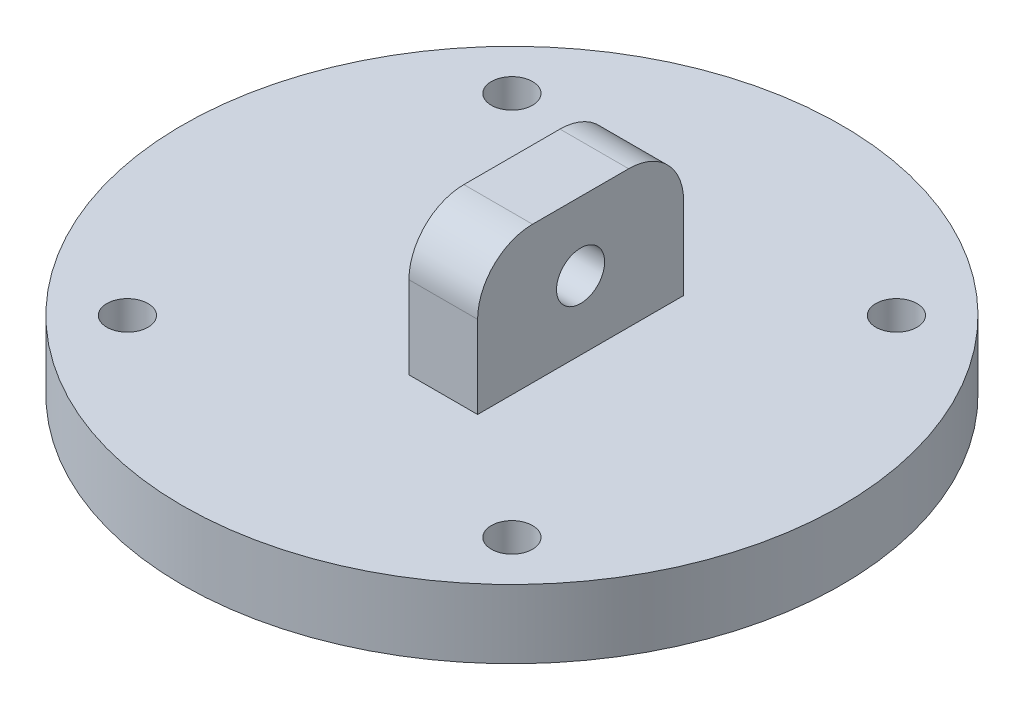
SolidWorks part; units mm, degrees
ref_plane "前视基准面" through (0, 0, 0) normal (0, 0, 1) x (1, 0, 0)
ref_plane "上视基准面" through (0, 0, 0) normal (0, 1, 0) x (1, 0, 0)
ref_plane "右视基准面" through (0, 0, 0) normal (1, 0, 0) x (0, 0, -1)
other "Configuration Table"
sketch "草图1" plane through (0, 0, 0) normal (0, 1, 0) x (1, 0, 0)
  line L0 (0, 34.1) -> (0, -32.0913) construction
  line L15 (-37.5602, 0) -> (46.169, 0) construction
  circle A1 centre (0, 0) radius 24
  dimension "D4" = 48
extrude "凸台-拉伸1" add sketch "草图1" along normal blind 5
sketch "草图2" plane through (0, 0, 0) normal (0, 1, 0) x (1, 0, 0)
  line L1 (-5, 7.5) -> (5, 7.5)
  line L2 (-5, 7.5) -> (-5, -7.5)
  line L3 (-5, -7.5) -> (5, -7.5)
  line L4 (5, 7.5) -> (5, -7.5)
  line L5 (-5, 7.5) -> (5, -7.5) construction
  line L6 (-5, -7.5) -> (5, 7.5) construction
  point P0 (0, 0)
  dimension "D1" = 10
  dimension "D2" = 15
extrude "凸台-拉伸2" add sketch "草图2" along normal blind 15
sketch "草图3" plane through (-5, 0, 0) normal (-1, 0, 0) x (0, 0, 1)
  line L1 (0, 17.9908) -> (0, -1.502) construction
  line L2 (-7.5, 10) -> (7.5, 10)
  line L3 (-7.5, 10) -> (7.5, 10) construction
  circle A0 centre (0, 10) radius 1.75
  dimension "D2" = 3.5
  dimension "D1" = 5
extrude "切除-拉伸1" cut sketch "草图3" against normal up to next
sketch "草图4" plane through (-5, 0, 0) normal (-1, 0, 0) x (0, 0, 1)
  line L1 (-10, 15) -> (10, 15)
  line L2 (-10, 15) -> (-10, 5)
  line L3 (-10, 5) -> (10, 5)
  line L4 (10, 15) -> (10, 5)
  line L5 (-10, 15) -> (10, 5) construction
  line L6 (-10, 5) -> (10, 15) construction
  point P0 (0, 10)
  dimension "D1" = 10
  dimension "D2" = 20
extrude "切除-拉伸2" cut sketch "草图4" against normal blind 5
sketch "草图5" plane through (0, 0, 0) normal (0, -1, 0) x (1, 0, 0)
  line L1 (-14, 14) -> (14, 14) construction
  line L2 (-14, 14) -> (-14, -14) construction
  line L3 (-14, -14) -> (14, -14) construction
  line L4 (14, 14) -> (14, -14) construction
  line L5 (-14, 14) -> (14, -14) construction
  line L6 (-14, -14) -> (14, 14) construction
  point P1 (14, -14)
  point P2 (-14, 14)
  point P3 (-14, -14)
  point P4 (14, 14)
  point P13 (14, -14)
  point P17 (-14, -14)
  point P19 (-14, 14)
  point P21 (14, 14)
  point P27 (0, 0)
  point P28 (0, 0)
  point P29 (0, 0)
  dimension "D1" = 28
  dimension "D2" = 28
hole_wizard "Ø3.0mm 暗销孔1" positions "草图5" profile "草图8" hole size "Ø3.0" standard "GB" end condition up to next
sketch "草图8" plane through (14, 0, 14) normal (1, 0, 0) x (0, 0, -1)
  line L0 (0, 0) -> (0, 5)
  line L1 (0, 5) -> (1.5, 5)
  line L2 (1.5, 5) -> (1.5, 0)
  line L5 (1.5, 0) -> (0, 0)
  line L11 (0, -6.35) -> (0, 107.95) construction
  dimension "通孔孔直径" = 3
  dimension "通孔孔深度" = 5
fillet "圆角1" radius 4 2 edges at (2.5, 15, 7.5) (2.5, 15, -7.5)
sketch "草图9" plane through (0, 0, 0) normal (0, -1, 0) x (1, 0, 0)
  line L0 (0, 72.0219) -> (0, -30.929) construction
  line L5 (-35.1086, 0) -> (40.4027, 0) construction
  line L6 (0, 0) -> (18.3848, 18.3848) construction
  line L7 (4.2426, -4.2426) -> (22.6274, 14.1421)
  line L8 (-4.2426, 4.2426) -> (14.1421, 22.6274)
  line L9 (14.1421, 22.6274) -> (22.6274, 14.1421)
  line L10 (4.2426, 4.2426) -> (22.6274, -14.1421)
  line L11 (22.6274, -14.1421) -> (14.1421, -22.6274)
  line L12 (-4.2426, -4.2426) -> (14.1421, -22.6274)
  line L13 (4.2426, -4.2426) -> (-14.1421, -22.6274)
  line L14 (-14.1421, -22.6274) -> (-22.6274, -14.1421)
  line L15 (-4.2426, 4.2426) -> (-22.6274, -14.1421)
  line L16 (-4.2426, -4.2426) -> (-22.6274, 14.1421)
  line L17 (-22.6274, 14.1421) -> (-14.1421, 22.6274)
  line L18 (4.2426, 4.2426) -> (-14.1421, 22.6274)
  point P0 (0, 0)
  point P28 (0, 0)
  circle M13 centre (0, 0) radius 24
  dimension "D1" = 45
  dimension "D2" = 6
  dimension "D3" = 6
  dimension "D4" = 26
  dimension "D5" = 4
extrude "切除-拉伸3" [suppressed] cut sketch "草图9" against normal blind 5 contours L18 L8 M13 | L7 L10 M13 | L12 L13 M13 | L15 L16 M13
